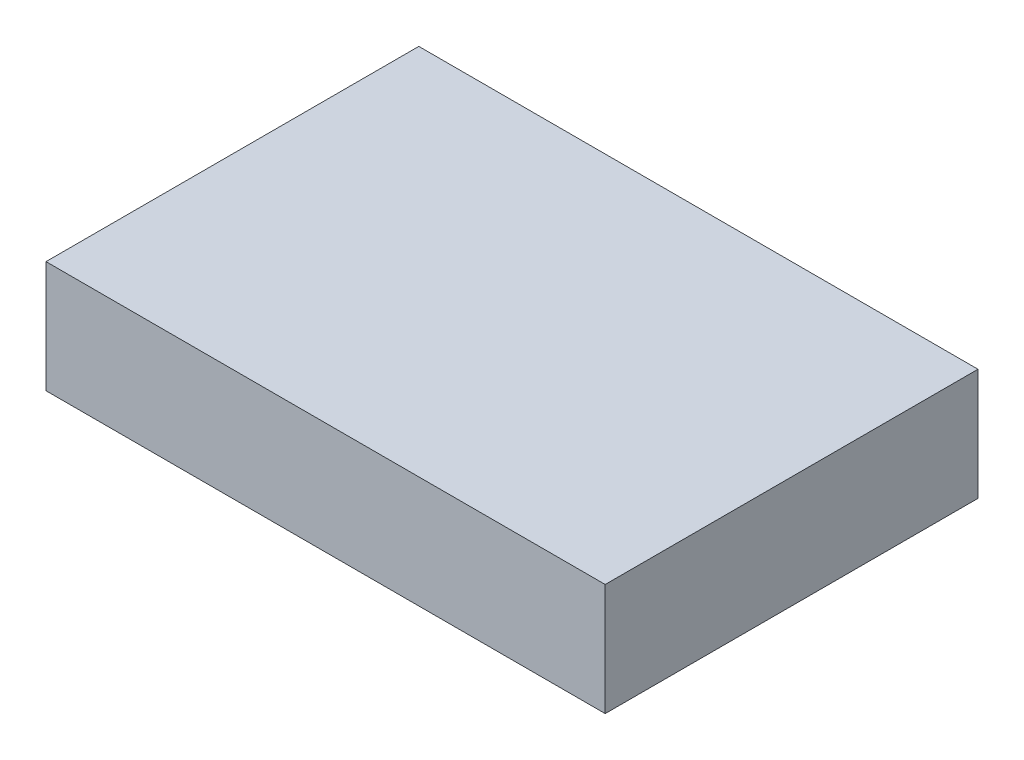
SolidWorks part; units mm, degrees
material "Acrílico (médio-alto impacto)"
ref_plane "Plano frontal" through (0, 0, 0) normal (0, 0, 1) x (1, 0, 0)
ref_plane "Plano superior" through (0, 0, 0) normal (0, 1, 0) x (1, 0, 0)
ref_plane "Plano direito" through (0, 0, 0) normal (1, 0, 0) x (0, 0, -1)
sketch "Esboço1" plane through (0, 0, 0) normal (0, 1, 0) x (1, 0, 0)
  line L1 (-30, -20) -> (30, -20)
  line L2 (-30, -20) -> (-30, 20)
  line L3 (-30, 20) -> (30, 20)
  line L4 (30, -20) -> (30, 20)
  line L5 (-30, -20) -> (30, 20) construction
  line L6 (-30, 20) -> (30, -20) construction
  point P0 (0, 0)
  dimension "D1" = 60
  dimension "D2" = 40
extrude "Ressalto-extrusão1" add sketch "Esboço1" along normal blind 12
